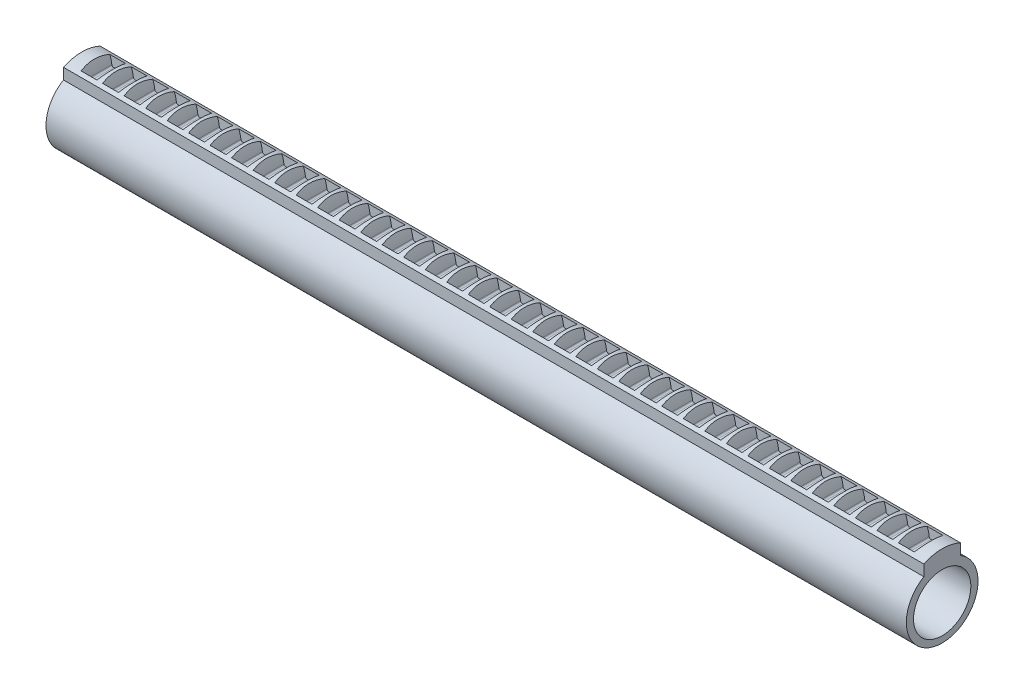
SolidWorks part; units mm, degrees
ref_plane "Front Plane" through (0, 0, 0) normal (0, 0, 1) x (1, 0, 0)
ref_plane "Top Plane" through (0, 0, 0) normal (0, 1, 0) x (1, 0, 0)
ref_plane "Right Plane" through (0, 0, 0) normal (1, 0, 0) x (0, 0, -1)
sketch "Sketch1" plane through (0, 0, 0) normal (1, 0, 0) x (0, 0, -1)
  line L0 (0, 9.6651) -> (0, -9.6651) construction
  line L1 (-8.933, 0) -> (8.933, 0) construction
  line L2 (-8.933, -7.5) -> (8.933, -7.5) construction
  line L4 (-3.2, 4.6548) -> (3.2, 4.6548)
  line L5 (-3.2, 4.6548) -> (-3.2, 6.7831)
  line L6 (-3.2, 6.7831) -> (3.2, 6.7831)
  line L7 (3.2, 4.6548) -> (3.2, 6.7831)
  line L8 (-3.2, 4.6548) -> (3.2, 6.7831) construction
  line L9 (-3.2, 6.7831) -> (3.2, 4.6548) construction
  circle A0 centre (0, 0) radius 7.5 construction
  circle A1 centre (0, -0.5) radius 6.25
  circle A4 centre (0, -0.65) radius 5
  arc A5 (-3.2, 6.7831) -> (3.2, 6.7831) centre (0, 0) cw
  point P8 (0, 0)
  point P11 (0, 0)
  point P12 (0, 5.7189)
  point P18 (0, -7.5)
  dimension "D1" = 15
  dimension "D2" = 12.5
  dimension "D3" = 10
  dimension "D5" = 0.15
  dimension "D6" = 7.4331
  dimension "D7" = 0.5
  dimension "D4" = 6.4
extrude "Boss-Extrude1" add sketch "Sketch1" along normal mid plane 150
sketch "Sketch2" plane through (0, 0, 3.2) normal (0, 0, 1) x (1, 0, 0)
  line L0 (0, -9.0492) -> (0, 9.0492) construction
  line L1 (-0.7199, 5.4131) -> (0.7199, 5.4131)
  line L2 (-2.58, 8.6931) -> (2.58, 8.6931)
  line L4 (-0.7199, 5.4131) -> (0.7199, 5.4131)
  line L5 (75, 6.7831) -> (-75, 6.7831) construction
  arc A0 (1.0184, 5.6838) -> (2.58, 8.6931) centre (5.5567, 5.2386) cw
  arc A1 (-1.0184, 5.6838) -> (-2.58, 8.6931) centre (-5.5567, 5.2386) ccw
  arc A3 (0.7199, 5.4131) -> (1.0184, 5.6838) centre (0.7199, 5.7131) ccw
  arc A4 (-1.0184, 5.6838) -> (-0.7199, 5.4131) centre (-0.7199, 5.7131) ccw
  point P11 (0, 5.4131)
  point P14 (1, 5.4131)
  point P17 (-1, 5.4131)
  line M14 (75, 6.7831) -> (-75, 6.7831)
  dimension "D3" = 1.58
  dimension "D5" = 4.56
  dimension "D6" = 5.16
  dimension "D7" = 0.3
  dimension "D1" = 1
  dimension "D2" = 1.37
  dimension "D4" = 3.28
extrude "Cut-Extrude1" cut sketch "Sketch2" against normal offset from surface (5 mm away) 0.7 from offset 0.7 contours L0 L2 A1 M14 | L0 A0 L2 M14 | L1 L0 A1 A4 M14 | L0 L4 A3 A0 M14 up to face at (0, 5.8259, -3.2) offset against normal yes
pattern_linear "LPattern1" count 20 spacing 3.75 along (-1, 0, 0) count 20 spacing 3.75 along (1, 0, 0) of "Cut-Extrude1"
